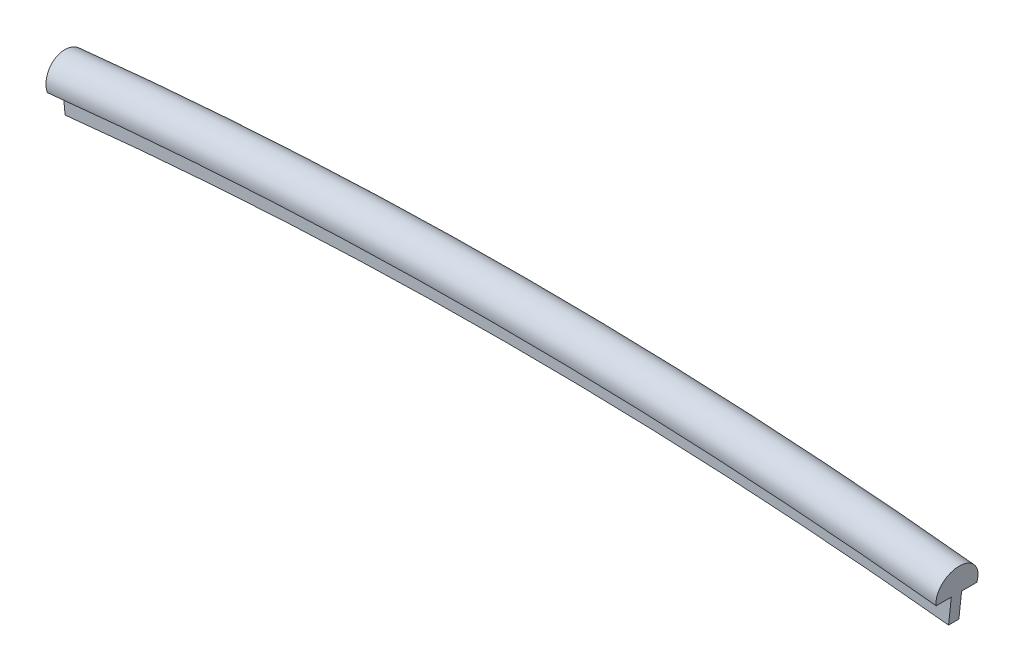
SolidWorks part; units mm, degrees
ref_plane "Front Plane" through (0, 0, 0) normal (0, 0, 1) x (1, 0, 0)
ref_plane "Top Plane" through (0, 0, 0) normal (0, 1, 0) x (1, 0, 0)
ref_plane "Right Plane" through (0, 0, 0) normal (1, 0, 0) x (0, 0, -1)
sketch "Sketch2" plane through (0, 0, 0) normal (1, 0, 0) x (0, 0, -1)
  line L0 (0, 241.3) -> (0, 0) construction
  line L2 (0, 241.3) -> (0, 239.8) construction
  line L3 (0, 239.8) -> (0.3, 239.8)
  line L4 (0, 239.8) -> (-0.3, 239.8)
  line L5 (-0.3, 239.8) -> (-0.3, 241.3)
  line L6 (0.3, 239.8) -> (0.3, 241.3)
  line L7 (0, 241.3) -> (0, 242.8) construction
  line L8 (-1.18, 241.3) -> (-0.3, 241.3)
  line L9 (0.3, 241.3) -> (1.18, 241.3)
  arc A0 (-1.18, 241.3) -> (1.18, 241.3) centre (0, 241.586) cw
  point P14 (0, 241.3)
ref_axis "Axis2" through (0, 0, 70.5976) along (0, 0, -1)
revolve "Revolve1" add sketch "Sketch2" angle 6.145 about axis through (0, 0, 70.5976) along (0, 0, -1)
